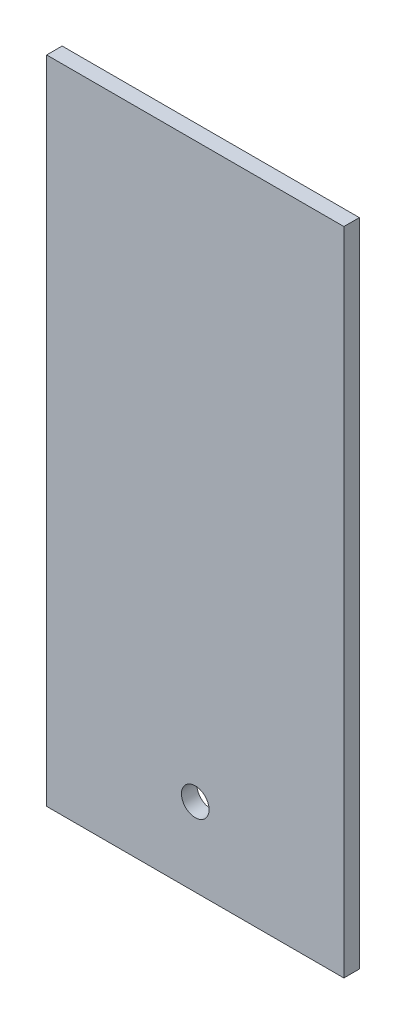
SolidWorks part; units mm, degrees
ref_plane "Plano frontal" through (0, 0, 0) normal (1, 0, 0) x (0, 1, 0)
ref_plane "Plano superior" through (0, 0, 0) normal (0, 0, 1) x (0, 1, 0)
ref_plane "Plano direito" through (0, 0, 0) normal (0, 1, 0) x (-1, 0, 0)
sketch "Esboço1" plane through (0, 0, 0) normal (0, 0, 1) x (0, 1, 0)
  line L1 (58.9, -26.9) -> (-58.9, -26.9)
  line L2 (58.9, -26.9) -> (58.9, 26.9)
  line L3 (58.9, 26.9) -> (-58.9, 26.9)
  line L4 (-58.9, -26.9) -> (-58.9, 26.9)
  line L5 (58.9, -26.9) -> (-58.9, 26.9) construction
  line L6 (58.9, 26.9) -> (-58.9, -26.9) construction
  point P0 (0, 0)
  dimension "D1" = 117.8
  dimension "D2" = 53.8
extrude "Ressalto-extrusão1" add sketch "Esboço1" along normal mid plane 2.8
sketch "Esboço2" plane through (0, 0, 1.4) normal (0, 0, 1) x (1, 0, 0)
  circle A0 centre (0, -44.7169) radius 2.5
  dimension "D1" = 5
extrude "Corte-extrusão1" cut sketch "Esboço2" against normal blind 2.8
